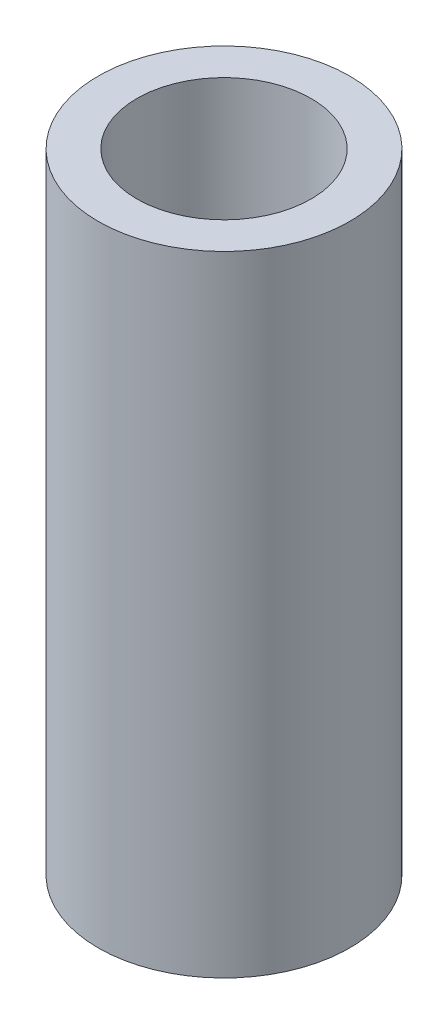
SolidWorks part; units mm, degrees
ref_plane "Alzado" through (0, 0, 0) normal (0, 0, 1) x (1, 0, 0)
ref_plane "Planta" through (0, 0, 0) normal (0, 1, 0) x (1, 0, 0)
ref_plane "Vista lateral" through (0, 0, 0) normal (1, 0, 0) x (0, 0, -1)
sketch "Croquis1" plane through (0, 0, 0) normal (0, 1, 0) x (1, 0, 0)
  circle A0 centre (0, 0) radius 4.5
  circle A1 centre (0, 0) radius 6.5
  dimension "D1" = 2
extrude "Saliente-Extruir1" add sketch "Croquis1" along normal blind 32.5
